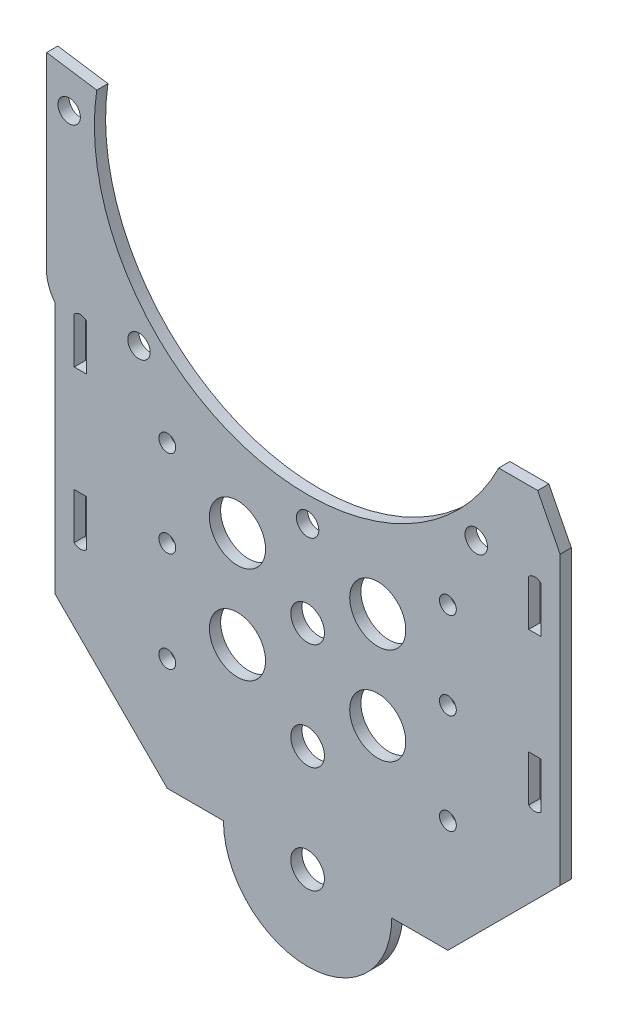
SolidWorks part; units mm, degrees
ref_plane "前视基准面" through (0, 0, 0) normal (0, 0, 1) x (1, 0, 0)
ref_plane "上视基准面" through (0, 0, 0) normal (0, 1, 0) x (1, 0, 0)
ref_plane "右视基准面" through (0, 0, 0) normal (1, 0, 0) x (0, 0, -1)
sketch "草图3" plane through (0, 0, 0) normal (0, 0, 1) x (1, 0, 0)
  line L0 (-45, -3.9902) -> (-45, -19.82)
  line L7 (0, -1.82) -> (0, 56) construction
  line L12 (-25, -1.9902) -> (0, -20.82) construction
  line L38 (-46.5, 63) -> (-37.5766, 61.6567)
  line L102 (-46.5, 63) -> (-46.5, 28.7735)
  line L105 (34.0612, 39.1525) -> (41, 39.1525)
  line L111 (-25, 13.5098) -> (0, -1.82) construction
  line L117 (-41.6, -1.9902) -> (-39.4, -1.9902)
  line L149 (41.6, 16.9098) -> (39.4, 25.1098) construction
  line L150 (41.6, 25.1098) -> (39.4, 16.9098) construction
  line L151 (40.5, 20.0098) -> (40.5, 25.0098) construction
  line L155 (-15, -39.82) -> (-25, -39.82) construction
  line L157 (41.6, -10.1902) -> (41.6, -1.9902)
  line L159 (39.4, -1.9902) -> (39.4, -10.1902)
  line L160 (39.4, 25.1098) -> (39.4, 16.9098)
  line L161 (41.6, 16.9098) -> (39.4, 16.9098)
  line L162 (41.6, 25.1098) -> (41.6, 16.9098)
  line L166 (41.6, -1.9902) -> (39.4, -1.9902)
  line L189 (-45, -3.9902) -> (-45, 25.1098)
  line L192 (45, -3.9902) -> (45, 31.3171)
  line L194 (45, 31.3171) -> (41, 39.1525)
  line L198 (-41.6, 25.1098) -> (-41.6, 16.9098)
  line L199 (-41.6, 16.9098) -> (-39.4, 16.9098)
  line L200 (-39.4, 25.1098) -> (-39.4, 16.9098)
  line L201 (-39.4, -1.9902) -> (-39.4, -10.1902)
  line L203 (-41.6, -10.1902) -> (-41.6, -1.9902)
  line L204 (-25, -39.82) -> (-15, -39.82)
  line L205 (25, -39.82) -> (15, -39.82)
  line L206 (45, -3.9902) -> (45, -19.82)
  line L207 (-45, -19.82) -> (-25, -39.82)
  line L209 (45, -19.82) -> (25, -39.82)
  arc A12 (-37.5766, 61.6567) -> (34.0612, 39.1525) centre (0, 56) ccw
  circle A16 centre (0, -1.82) radius 3
  circle A17 centre (0, 13.5) radius 2
  circle A18 centre (-30.052, 25.948) radius 2
  circle A19 centre (-42.5, 56) radius 2
  circle A24 centre (30.052, 25.948) radius 2
  circle A25 centre (-30.052, 86.052) radius 2 [skipped]
  circle A26 centre (0, 98.5) radius 2 [skipped]
  circle A27 centre (30.052, 86.052) radius 2 [skipped]
  circle A28 centre (42.5, 56) radius 2 [skipped]
  circle A29 centre (0, -20.82) radius 3
  circle A30 centre (0, -39.82) radius 3
  arc A32 (-15, -39.82) -> (15, -39.82) centre (0, -39.82) ccw
  circle A33 centre (-25, -1.9902) radius 1.5
  circle A34 centre (-25, -19.82) radius 1.5
  circle A35 centre (-25, 13.5098) radius 1.5
  circle A36 centre (25, 13.5098) radius 1.5
  circle A37 centre (25, -19.82) radius 1.5
  circle A38 centre (25, -1.9902) radius 1.5
  circle A39 centre (-12.5, -11.4051) radius 5
  circle A40 centre (-12.5, 5.8449) radius 5
  circle A41 centre (12.5, 5.8449) radius 5
  circle A42 centre (12.5, -11.4051) radius 5
  arc A43 (-41.6, 25.1098) -> (-39.4, 25.1098) centre (-40.5, 24.0098) cw
  arc A44 (-41.6, -10.1902) -> (-39.4, -10.1902) centre (-40.5, -9.0902) ccw
  arc A45 (39.4, 25.1098) -> (41.6, 25.1098) centre (40.5, 24.0098) cw
  arc A46 (39.4, -10.1902) -> (41.6, -10.1902) centre (40.5, -9.0902) ccw
  circle A47 centre (0, 56) radius 42.5 construction
  spline S0 degree 2 poles (-45, 25.1098) (-46.2742, 26.7251) (-46.5, 28.7735) knots 0 0 0 1 1 1
  point P52 (40.5, 22.5098)
  point P70 (0, 0)
extrude "凸台-拉伸1" add sketch "草图3" along normal blind 2
sketch "草图5" plane through (0, 0, 0) normal (0, 0, -1) x (-1, 0, 0)
  line L0 (0, 0.18) -> (0, 5.18)
  line L1 (0, 5.18) -> (-15, 5.18)
  line L2 (-15, 5.18) -> (-15, -9.82)
  point P0 (0, -1.82)
